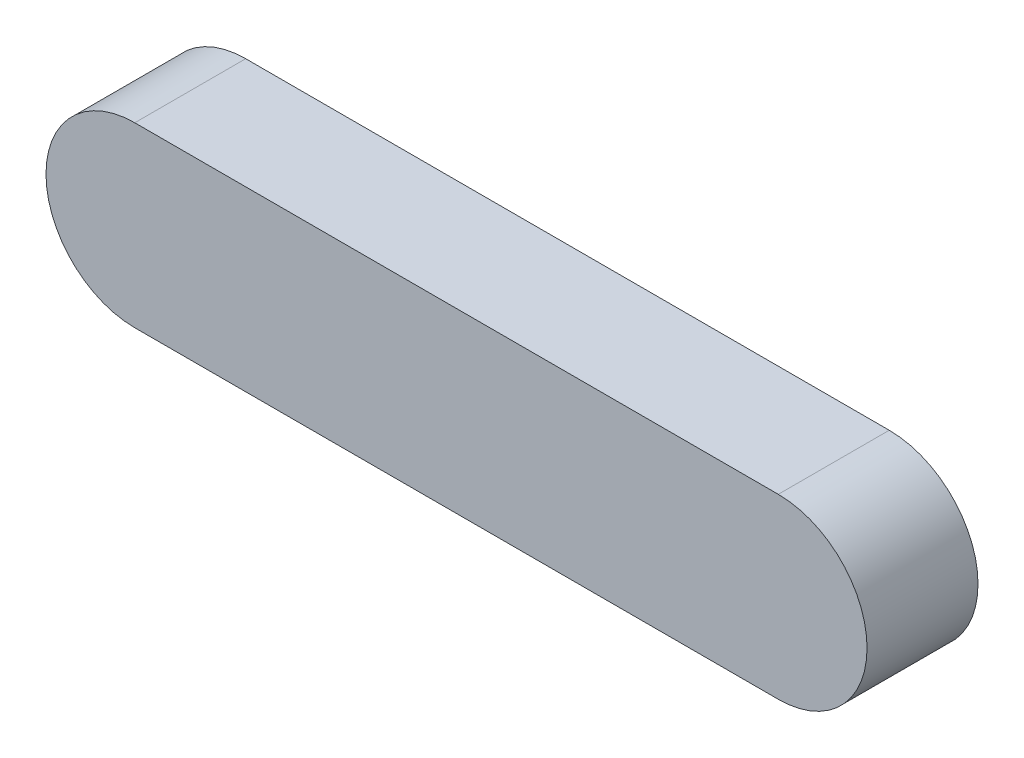
SolidWorks part; units mm, degrees
ref_plane "前视基准面" through (0, 0, 0) normal (0, 0, 1) x (1, 0, 0)
ref_plane "上视基准面" through (0, 0, 0) normal (0, 1, 0) x (1, 0, 0)
ref_plane "右视基准面" through (0, 0, 0) normal (1, 0, 0) x (0, 0, -1)
other "Configuration Table"
sketch "草图1" plane through (0, 0, 0) normal (0, 0, 1) x (1, 0, 0)
  line L0 (0, 0) -> (58, 0) construction
  line L1 (0, 8) -> (58, 8)
  line L2 (0, -8) -> (58, -8)
  arc A0 (0, 8) -> (0, -8) centre (0, 0) ccw
  arc A1 (58, -8) -> (58, 8) centre (58, 0) ccw
  point P3 (29, 0)
  dimension "D1" = 58
  dimension "D2" = 16
extrude "凸台-拉伸1" add sketch "草图1" along normal blind 10
